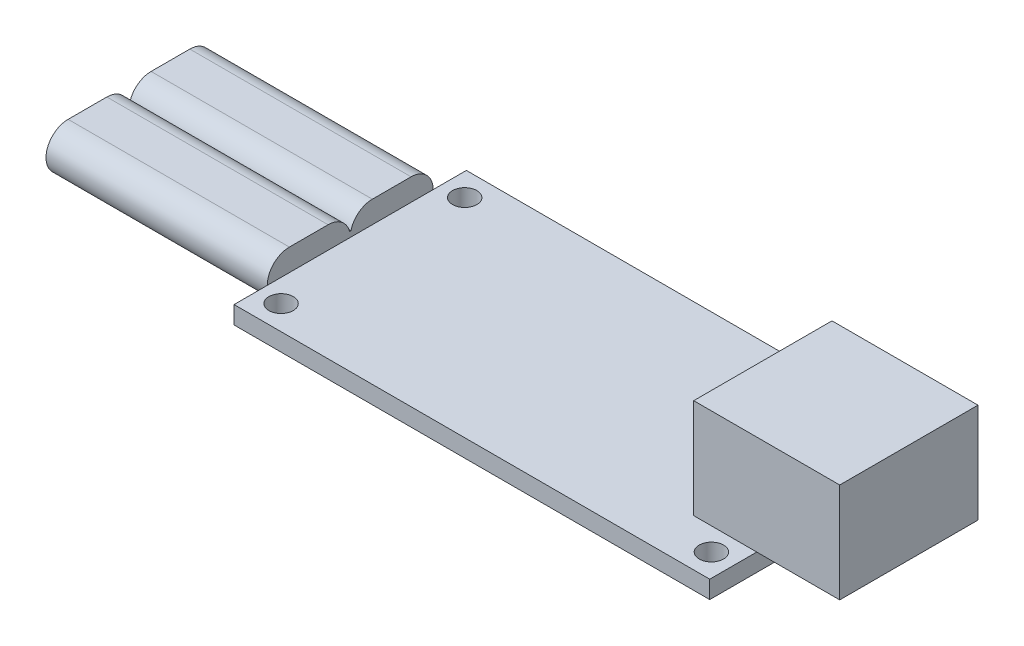
SolidWorks part; units mm, degrees
ref_plane "Płaszczyzna przednia" through (0, 0, 0) normal (0, 0, 1) x (1, 0, 0)
ref_plane "Płaszczyzna górna" through (0, 0, 0) normal (0, 1, 0) x (1, 0, 0)
ref_plane "Płaszczyzna prawa" through (0, 0, 0) normal (1, 0, 0) x (0, 0, -1)
sketch "Sketch1" plane through (0, 0, 0) normal (0, 1, 0) x (1, 0, 0)
  line L0 (21.5, 21) -> (21.5, 10.5) construction
  line L1 (0, 0) -> (43, 0)
  line L2 (0, 0) -> (0, 21)
  line L3 (0, 21) -> (43, 21)
  line L4 (43, 0) -> (43, 21)
  line L5 (21.5, 10.5) -> (0, 10.5) construction
  line L6 (2.05, 18.8) -> (40.95, 2.2) construction
  line L7 (40.95, 18.8) -> (2.05, 2.2) construction
  circle A0 centre (2.05, 18.8) radius 1.1
  circle A1 centre (40.95, 18.8) radius 1.1
  circle A2 centre (40.95, 2.2) radius 1.1
  circle A3 centre (2.05, 2.2) radius 1.1
  point P16 (21.5, 10.5)
  dimension "D3" = 2.2
  dimension "D6" = 38.9
  dimension "D7" = 16.6
  dimension "D1" = 21
  dimension "D2" = 43
  dimension "D4" = 2
  dimension "D5" = 2
extrude "Boss-Extrude1" add sketch "Sketch1" along normal blind 1.6
sketch "Sketch2" plane through (0, 0, 0) normal (-1, 0, 0) x (0, 0, 1)
  line L0 (-21, 1.6) -> (0, 1.6) construction
  line L1 (-12.5, 1.6) -> (-16, 1.6) construction
  line L2 (-12.5, -0.4) -> (-16, -0.4)
  line L3 (-12.5, 3.6) -> (-16, 3.6)
  line L4 (-8.5, 1.6) -> (-5, 1.6) construction
  line L5 (-8.5, 3.6) -> (-5, 3.6)
  line L6 (-8.5, -0.4) -> (-5, -0.4)
  line L7 (-14.25, 1.6) -> (-6.75, 1.6) construction
  line L8 (-10.5, 0) -> (-10.5, 1.6) construction
  line L9 (-21, 0) -> (0, 0) construction
  circle A0 centre (-14.25, 1.6) radius 2.0409 construction
  circle A1 centre (-6.75, 1.6) radius 1.5789 construction
  arc A2 (-12.5, -0.4) -> (-12.5, 3.6) centre (-12.5, 1.6) ccw
  arc A3 (-16, 3.6) -> (-16, -0.4) centre (-16, 1.6) ccw
  arc A4 (-8.5, 3.6) -> (-8.5, -0.4) centre (-8.5, 1.6) ccw
  arc A5 (-5, -0.4) -> (-5, 3.6) centre (-5, 1.6) ccw
  circle A6 centre (-10.5, 1.6) radius 0.5
  point P8 (-14.25, 1.6)
  point P15 (-6.75, 1.6)
  point P20 (-10.5, 1.6)
  point P21 (-18, 1.6)
  point P22 (-3, 1.6)
  line M13 (-21, 0) -> (0, 0)
  line M15 (0, 1.6) -> (-21, 1.6)
  dimension "D1" = 15
  dimension "D4" = 1
  dimension "D2" = 7.5
  dimension "D3" = 4
extrude "Boss-Extrude2" add sketch "Sketch2" along normal blind 20 contours A6 A2 L3 A3 M15 | A6 A3 A2 M15 M13 | A3 L2 A2 M13 | A2 A6 M15 | A4 A6 A2 | A6 A4 M15 | A4 A6 M15 | A6 A2 M15 | A2 A6 A4 | A6 A4 A5 M13 M15 | A6 A5 L5 A4 M15 | L6 A5 A4 M13
sketch "Sketch3" plane through (0, 1.6, 0) normal (0, 1, 0) x (1, 0, 0)
  line L0 (0, 10.5) -> (37.3, 10.5) construction
  line L1 (37.3, 16.75) -> (50.5, 16.75)
  line L2 (37.3, 16.75) -> (37.3, 4.25)
  line L3 (37.3, 4.25) -> (50.5, 4.25)
  line L4 (50.5, 16.75) -> (50.5, 4.25)
  line L5 (0, 18) -> (0, 3) construction
  dimension "D1" = 12.5
  dimension "D2" = 13.2
  dimension "D3" = 50.5
extrude "Boss-Extrude3" add sketch "Sketch3" along normal blind 9
